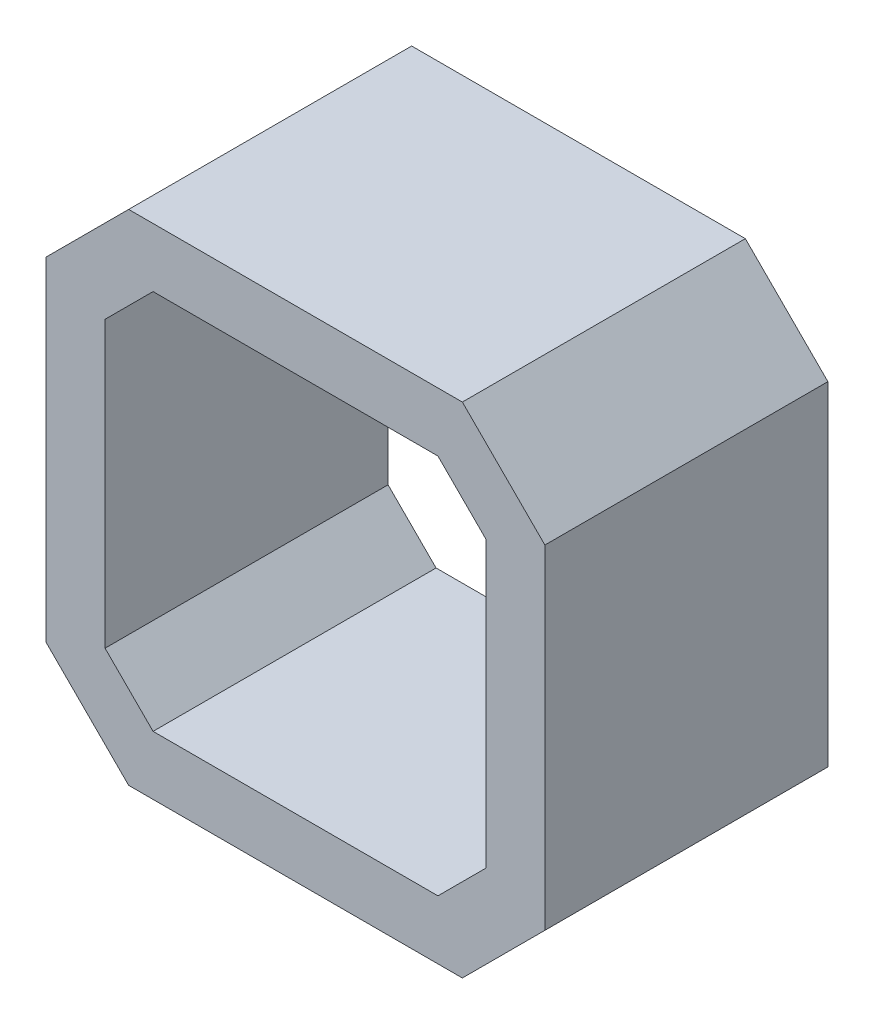
SolidWorks part; units mm, degrees
ref_plane "Front Plane" through (0, 0, 0) normal (0, 0, 1) x (1, 0, 0)
ref_plane "Top Plane" through (0, 0, 0) normal (0, 1, 0) x (1, 0, 0)
ref_plane "Right Plane" through (0, 0, 0) normal (1, 0, 0) x (0, 0, -1)
sketch "Sketch1" plane through (0, 0, 0) normal (0, 0, 1) x (1, 0, 0)
  line L0 (-14.15, 21.15) -> (-21.15, 14.15)
  line L1 (14.15, -21.15) -> (-14.15, -21.15)
  line L2 (21.15, -14.15) -> (21.15, 14.15)
  line L3 (14.15, 21.15) -> (-14.15, 21.15)
  line L4 (-21.15, -14.15) -> (-21.15, 14.15)
  line L5 (21.15, -21.15) -> (-21.15, 21.15) construction
  line L6 (21.15, 21.15) -> (-21.15, -21.15) construction
  line L7 (-14.15, -21.15) -> (-21.15, -14.15)
  line L8 (21.15, -14.15) -> (14.15, -21.15)
  line L9 (21.15, 14.15) -> (14.15, 21.15)
  line L10 (-12.0789, 16.15) -> (-16.15, 12.0789)
  line L11 (-16.15, -12.0789) -> (-16.15, 12.0789)
  line L12 (-12.0789, -16.15) -> (-16.15, -12.0789)
  line L13 (12.0789, -16.15) -> (-12.0789, -16.15)
  line L14 (16.15, -12.0789) -> (12.0789, -16.15)
  line L15 (16.15, -12.0789) -> (16.15, 12.0789)
  line L16 (16.15, 12.0789) -> (12.0789, 16.15)
  line L17 (12.0789, 16.15) -> (-12.0789, 16.15)
  point P0 (0, 0)
  dimension "D1" = 42.3
  dimension "D2" = 5
extrude "Boss-Extrude1" add sketch "Sketch1" along normal blind 24
